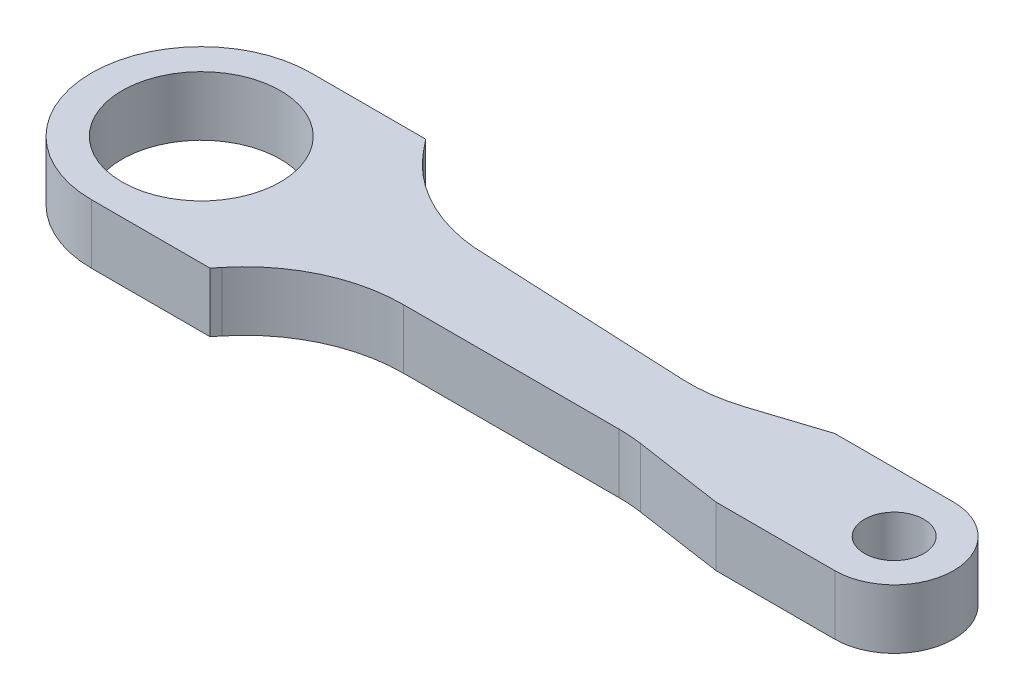
SolidWorks part; units mm, degrees
ref_plane "Front Plane" through (0, 0, 0) normal (0, 0, 1) x (1, 0, 0)
ref_plane "Top Plane" through (0, 0, 0) normal (0, 1, 0) x (1, 0, 0)
ref_plane "Right Plane" through (0, 0, 0) normal (1, 0, 0) x (0, 0, -1)
sketch "Sketch1" plane through (0, 0, 0) normal (0, 1, 0) x (1, 0, 0)
  line L0 (8.1169, 3) -> (4.7012, 1.8993)
  line L1 (-20.8831, 5.5452) -> (-15.0916, 5.5452)
  line L2 (-20.8831, -5.5452) -> (-14.895, -5.5452)
  line L3 (14.1169, 3) -> (8.1169, 3)
  line L4 (14.1169, -3) -> (8.1169, -3)
  line L5 (1.8761, 1.5223) -> (-8.404, 2)
  line L6 (8.1169, -3) -> (3.6508, -2.3424)
  line L7 (2.4854, -2.257) -> (-8.416, -2.257)
  line L8 (-14.6164, 4.9595) -> (-15.0916, 5.5452)
  line L9 (-29.5581, 0) -> (23.0899, 0) construction
  line L14 (-14.6283, -5.2165) -> (-14.895, -5.5452)
  arc A2 (-20.8831, 5.5452) -> (-20.8831, -5.5452) centre (-20.8831, 0) ccw
  circle A3 centre (-20.8831, 0) radius 4
  circle A6 centre (14.1169, 0) radius 1.5
  arc A7 (14.1169, -3) -> (14.1169, 3) centre (14.1169, 0) ccw
  arc A8 (-8.404, 2) -> (-14.6164, 4.9595) centre (-8.404, 10) cw
  arc A9 (-14.6283, -5.2165) -> (-8.416, -2.257) centre (-8.416, -10.257) cw
  arc A10 (3.6508, -2.3424) -> (2.4854, -2.257) centre (2.4854, -10.257) ccw
  arc A11 (4.7012, 1.8993) -> (1.8761, 1.5223) centre (2.2475, 9.5137) cw
  point P27 (-2.9653, -2.257)
  dimension "D1" = 8
  dimension "D4" = 6
  dimension "D5" = 6
  dimension "D6" = 8
  dimension "D7" = 4
  dimension "D3" = 35
  dimension "D2" = 8
extrude "Boss-Extrude1" add sketch "Sketch1" along normal blind 3
